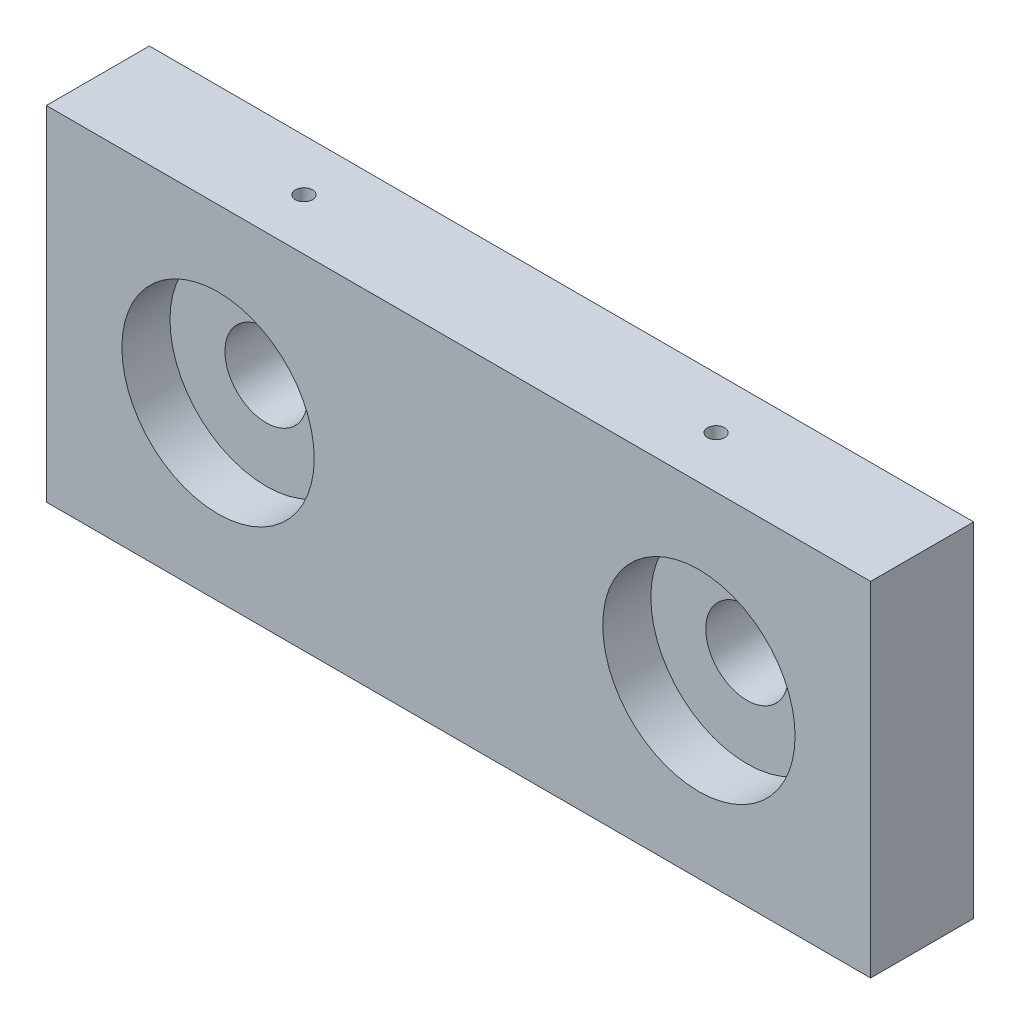
SolidWorks part; units mm, degrees
ref_plane "前视基准面" through (0, 0, 0) normal (0, 0, 1) x (1, 0, 0)
ref_plane "上视基准面" through (0, 0, 0) normal (0, 1, 0) x (1, 0, 0)
ref_plane "右视基准面" through (0, 0, 0) normal (1, 0, 0) x (0, 0, -1)
sketch "草图1" plane through (0, 0, 0) normal (0, 0, 1) x (1, 0, 0)
  line L0 (60, 25) -> (-60, -25) construction
  line L1 (-60, -25) -> (60, -25)
  line L2 (-60, -25) -> (-60, 25)
  line L3 (-60, 25) -> (60, 25)
  line L4 (60, -25) -> (60, 25)
  line L5 (-60, 25) -> (60, -25) construction
  point P4 (0, 0)
  dimension "D1" = 120
  dimension "D2" = 50
extrude "凸台-拉伸1" add sketch "草图1" along normal blind 15
sketch "草图2" plane through (0, 0, 15) normal (0, 0, 1) x (1, 0, 0)
  line L0 (0, 25) -> (0, -25) construction
  line L1 (60, 25) -> (-60, 25) construction
  line L2 (-60, -25) -> (60, -25) construction
  line L3 (-60, 0) -> (60, 0) construction
  line L4 (-60, 25) -> (-60, -25) construction
  line L5 (60, -25) -> (60, 25) construction
  circle A0 centre (-35, 0) radius 6
  circle A1 centre (35, 0) radius 6
  dimension "D2" = 12
  dimension "D3" = 70
extrude "切除-拉伸1" cut sketch "草图2" against normal up to next
sketch "草图3" plane through (0, 0, 15) normal (0, 0, 1) x (1, 0, 0)
  line L0 (0, 0) -> (35, 0) construction
  circle A1 centre (35, 0) radius 11
  circle A3 centre (-35, 0) radius 11
  dimension "D1" = 70
  dimension "D3" = 22
  dimension "D2" = 35
sketch "草图12" plane through (0, 25, 0) normal (0, 1, 0) x (1, 0, 0)
  line L0 (0, 0) -> (60, -15) construction
  line L1 (60, 0) -> (0, -15) construction
  line L2 (60, -15) -> (-60, -15) construction
  line L3 (0, 0) -> (0, -15) construction
  point P9 (30, -7.5)
  point P10 (-30, -7.5)
hole_wizard "M3 螺纹孔1" positions "草图13" profile "草图14" tap size "M3" standard "GB"
sketch "草图13" plane through (0, 25, 0) normal (0, 1, 0) x (1, 0, 0)
  line L0 (0, 0) -> (60, -15) construction
  point P0 (30, -7.5)
  point P4 (-30, -7.5)
sketch "草图14" plane through (30, 25, 7.5) normal (1, 0, 0) x (0, 0, 1)
  line L0 (0, 0) -> (0, 5.7511)
  line L1 (0, 5.7511) -> (1.25, 5)
  line L2 (1.25, 5) -> (1.25, 0)
  line L5 (1.25, 0) -> (0, 0)
  line L10 (0, 5.7511) -> (-1.25, 5) construction
  line L11 (0, -6.35) -> (0, 107.95) construction
  dimension "螺纹孔钻头直径" = 2.5
  dimension "螺纹孔钻头深度" = 5
  dimension "导头角度" = 118
cosmetic thread "孔螺蚊线1" parameters "D1"=5, "D2"=3
cosmetic thread "孔螺蚊线2" parameters "D1"=5, "D2"=3
hole_wizard "M3 螺纹孔2" positions "草图18" profile "草图17" tap size "M3" standard "GB"
sketch "草图18" plane through (0, -25, 0) normal (0, -1, 0) x (-1, 0, 0)
  line L0 (0, 0) -> (-60, -15) construction
  point P0 (-30, -7.5)
  point P4 (30, -7.5)
sketch "草图17" plane through (30, -25, 7.5) normal (1, 0, 0) x (0, 0, -1)
  line L0 (0, 0) -> (0, 5.7511)
  line L1 (0, 5.7511) -> (1.25, 5)
  line L2 (1.25, 5) -> (1.25, 0)
  line L5 (1.25, 0) -> (0, 0)
  line L10 (0, 5.7511) -> (-1.25, 5) construction
  line L11 (0, -6.35) -> (0, 107.95) construction
  dimension "螺纹孔钻头直径" = 2.5
  dimension "螺纹孔钻头深度" = 5
  dimension "导头角度" = 118
cosmetic thread "孔螺蚊线3" parameters "D1"=5, "D2"=3
cosmetic thread "孔螺蚊线4" parameters "D1"=5, "D2"=3
sketch "草图19" plane through (0, 0, 15) normal (0, 0, 1) x (1, 0, 0)
  circle A0 centre (-35, 0) radius 14
  circle A1 centre (35, 0) radius 14
extrude "切除-拉伸3" cut sketch "草图19" against normal blind 7
